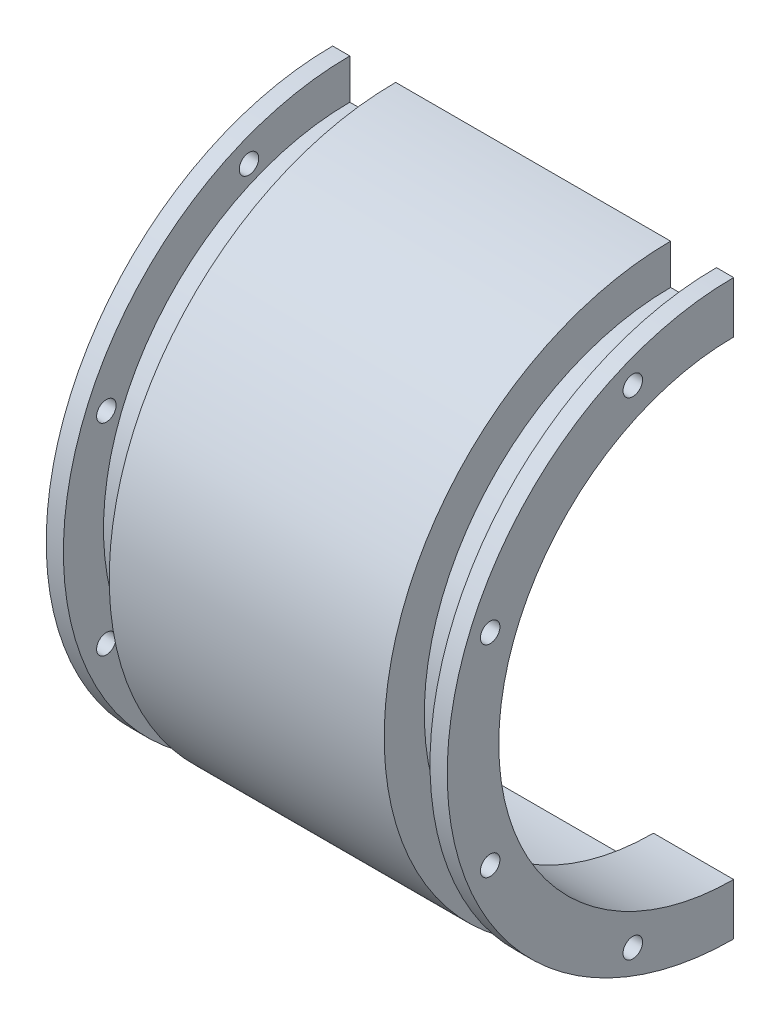
SolidWorks part; units mm, degrees
ref_plane "正面" through (0, 0, 0) normal (0, 0, 1) x (1, 0, 0)
ref_plane "平面" through (0, 0, 0) normal (0, 1, 0) x (1, 0, 0)
ref_plane "右側面" through (0, 0, 0) normal (1, 0, 0) x (0, 0, -1)
sketch "ｽｹｯﾁ1" plane through (0, 0, 0) normal (0, 0, 1) x (1, 0, 0)
  line L0 (-35, 41) -> (-21, 41)
  line L1 (-21, 41) -> (-21, 47)
  line L2 (-21, 47) -> (21, 47)
  line L3 (21, 47) -> (21, 41)
  line L4 (21, 41) -> (35, 41)
  line L5 (35, 41) -> (35, 50)
  line L6 (35, 50) -> (32, 50)
  line L7 (32, 50) -> (32, 43)
  line L8 (32, 43) -> (24, 43)
  line L9 (24, 43) -> (24, 50)
  line L10 (24, 50) -> (-24, 50)
  line L11 (-24, 50) -> (-24, 43)
  line L12 (-24, 43) -> (-32, 43)
  line L13 (-32, 43) -> (-32, 50)
  line L14 (-32, 50) -> (-35, 50)
  line L15 (-35, 50) -> (-35, 41)
  point P3 (0, 47)
  point P18 (0, 50)
  dimension "D1" = 3
  dimension "D2" = 9
  dimension "D3" = 2
  dimension "D4" = 70
  dimension "D5" = 3
  dimension "D6" = 3
  dimension "D7" = 8
  dimension "D8" = 50
sketch "ｽｹｯﾁ2" plane through (0, 0, 0) normal (0, 0, 1) x (1, 0, 0)
  line L0 (-50, 0) -> (50, 0)
  point P3 (0, 0)
  dimension "D1" = 100
revolve "回転1" add sketch "ｽｹｯﾁ1" angle 180 about L0
hole_wizard "M3 すきま穴1" positions "ｽｹｯﾁ5" profile "ｽｹｯﾁ6" hole size "M3" standard "JIS"
sketch "ｽｹｯﾁ5" plane through (-35, 0, 0) normal (-1, 0, 0) x (0, 0, 1)
  line L5 (0, 0) -> (17.6034, -42.4985)
  line L7 (0, -50) -> (0, -41) construction
  circle A0 centre (0, 0) radius 41 construction
  point P0 (17.6034, -42.4985)
  dimension "D1" = 46
  dimension "D2" = 22.5
sketch "ｽｹｯﾁ6" plane through (-35, -42.4985, 17.6034) normal (0, 1, 0) x (0, 0, 1)
  line L0 (0, 0) -> (0, 3)
  line L1 (0, 3) -> (1.7, 3)
  line L2 (1.7, 3) -> (1.7, 0)
  line L5 (1.7, 0) -> (0, 0)
  line L11 (0, -6.35) -> (0, 107.95) construction
  dimension "通し穴の直径" = 3.4
  dimension "通し穴の深さ" = 3
pattern_circular "円形ﾊﾟﾀｰﾝ1" count 4 every 45 about axis through (0, 0, 0) along (1, 0, 0) of "M3 すきま穴1"
mirror "ﾐﾗｰ1" about plane through (0, 0, 0) normal (1, 0, 0) of "円形ﾊﾟﾀｰﾝ1", "M3 すきま穴1"
fillet "ﾌｨﾚｯﾄ1" radius 5 2 edges at (-21, 0, 47) (21, 0, 47)
